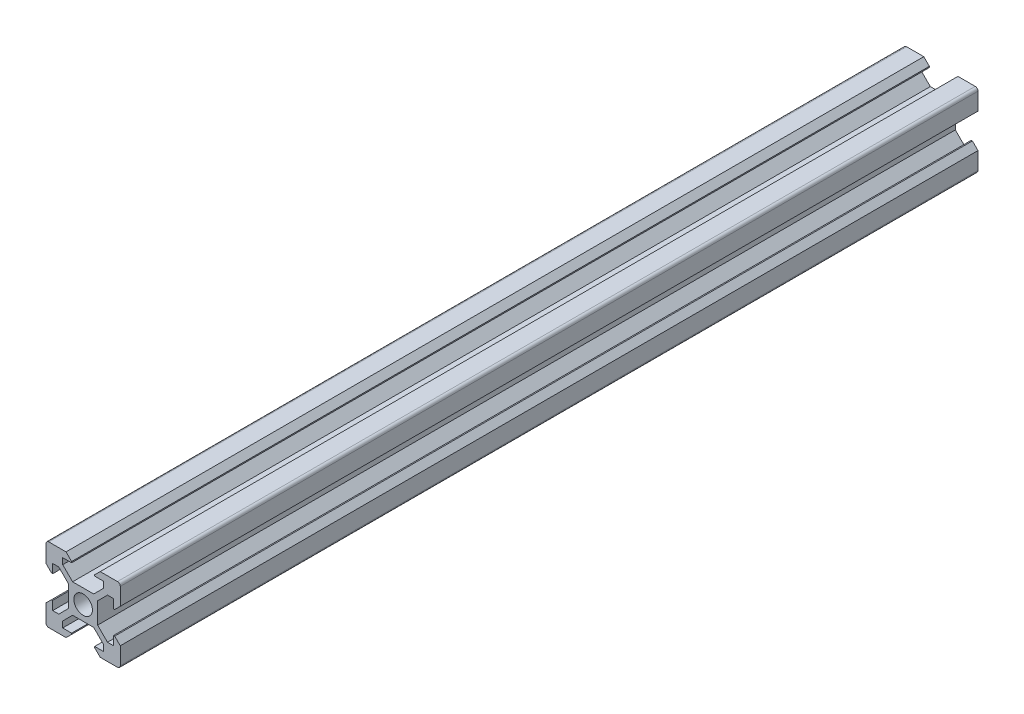
SolidWorks part; units mm, degrees
other "Markup1"
sketch "Sketch1" plane through (10, 10, 480) normal (0.5774, 0.5773, 0.5774) x (0.7071, 0, -0.7071)
ref_plane "Alzado" through (0, 0, 0) normal (0, 0, 1) x (1, 0, 0)
ref_plane "Planta" through (0, 0, 0) normal (0, 1, 0) x (1, 0, 0)
ref_plane "Vista lateral" through (0, 0, 0) normal (1, 0, 0) x (0, 0, -1)
sketch "Croquis1" plane through (0, 0, 0) normal (0, 0, 1) x (1, 0, 0)
  line L0 (-4.6, 10) -> (-3.1, 8.5)
  line L3 (-4.6, 10) -> (-9.25, 10)
  line L5 (-3.1, 8.5) -> (-3.1, 8.2)
  line L6 (-3.1, 8.2) -> (-5.5, 8.2)
  line L7 (-5.5, 8.2) -> (-5.5, 6.5607)
  line L8 (-5.5, 6.5607) -> (-2.84, 3.9007)
  line L9 (-2.84, 3.9007) -> (0, 3.9007)
  line L10 (0, 0) -> (-15.3499, 15.3499) construction
  line L11 (-3.9007, 2.84) -> (-3.9007, 0)
  line L12 (-6.5607, 5.5) -> (-3.9007, 2.84)
  line L13 (-8.2, 5.5) -> (-6.5607, 5.5)
  line L14 (-8.2, 3.1) -> (-8.2, 5.5)
  line L15 (-8.5, 3.1) -> (-8.2, 3.1)
  line L16 (-10, 4.6) -> (-10, 9.25)
  line L17 (-10, 4.6) -> (-8.5, 3.1)
  line L18 (10, 4.6) -> (8.5, 3.1)
  line L19 (10, 4.6) -> (10, 9.25)
  line L20 (8.5, 3.1) -> (8.2, 3.1)
  line L21 (8.2, 3.1) -> (8.2, 5.5)
  line L22 (8.2, 5.5) -> (6.5607, 5.5)
  line L23 (6.5607, 5.5) -> (3.9007, 2.84)
  line L24 (3.9007, 2.84) -> (3.9007, 0)
  line L25 (5.5, 6.5607) -> (2.84, 3.9007)
  line L26 (5.5, 8.2) -> (5.5, 6.5607)
  line L27 (3.1, 8.2) -> (5.5, 8.2)
  line L28 (3.1, 8.5) -> (3.1, 8.2)
  line L29 (4.6, 10) -> (9.25, 10)
  line L30 (4.6, 10) -> (3.1, 8.5)
  line L31 (2.84, 3.9007) -> (0, 3.9007)
  line L32 (4.6, -10) -> (3.1, -8.5)
  line L33 (4.6, -10) -> (9.25, -10)
  line L34 (3.1, -8.5) -> (3.1, -8.2)
  line L35 (3.1, -8.2) -> (5.5, -8.2)
  line L36 (5.5, -8.2) -> (5.5, -6.5607)
  line L37 (5.5, -6.5607) -> (2.84, -3.9007)
  line L38 (2.84, -3.9007) -> (0, -3.9007)
  line L39 (6.5607, -5.5) -> (3.9007, -2.84)
  line L40 (8.2, -5.5) -> (6.5607, -5.5)
  line L41 (8.2, -3.1) -> (8.2, -5.5)
  line L42 (8.5, -3.1) -> (8.2, -3.1)
  line L43 (10, -4.6) -> (10, -9.25)
  line L44 (10, -4.6) -> (8.5, -3.1)
  line L45 (3.9007, -2.84) -> (3.9007, 0)
  line L46 (-10, -4.6) -> (-8.5, -3.1)
  line L47 (-10, -4.6) -> (-10, -9.25)
  line L48 (-8.5, -3.1) -> (-8.2, -3.1)
  line L49 (-8.2, -3.1) -> (-8.2, -5.5)
  line L50 (-8.2, -5.5) -> (-6.5607, -5.5)
  line L51 (-6.5607, -5.5) -> (-3.9007, -2.84)
  line L52 (-3.9007, -2.84) -> (-3.9007, 0)
  line L53 (-5.5, -6.5607) -> (-2.84, -3.9007)
  line L54 (-5.5, -8.2) -> (-5.5, -6.5607)
  line L55 (-3.1, -8.2) -> (-5.5, -8.2)
  line L56 (-3.1, -8.5) -> (-3.1, -8.2)
  line L57 (-4.6, -10) -> (-9.25, -10)
  line L58 (-4.6, -10) -> (-3.1, -8.5)
  line L59 (-2.84, -3.9007) -> (0, -3.9007)
  circle A0 centre (0, 0) radius 2.5
  arc A1 (-9.25, 10) -> (-10, 9.25) centre (-9.25, 9.25) ccw
  arc A2 (10, 9.25) -> (9.25, 10) centre (9.25, 9.25) ccw
  arc A3 (9.25, -10) -> (10, -9.25) centre (9.25, -9.25) ccw
  arc A4 (-10, -9.25) -> (-9.25, -10) centre (-9.25, -9.25) ccw
  point P18 (-10, 10)
  point P37 (10, 10)
  point P55 (10, -10)
  point P73 (-10, -10)
  point P79 (0, 0)
  dimension "D1" = 5
  dimension "D5" = 0.75
  dimension "D2" = 10
  dimension "D3" = 10
  dimension "D4" = 4.6
  dimension "D6" = 5.5
  dimension "D7" = 135
  dimension "D8" = 0.75
  dimension "D9" = 225
  dimension "D10" = 2.84
  dimension "D11" = 1.8
  dimension "D12" = 3.1
  dimension "D13" = 4
extrude "Saliente-Extruir1" add sketch "Croquis1" along normal blind 480
sketch "Sketch2" plane through (0, 0, 0) normal (1, 0, 0) x (0, 0, -1)
  line L0 (-249, 40.7698) -> (-249, -37.1573) construction
  line L1 (-249, -13.3929) -> (249, -13.3929)
  line L2 (-249, -13.3929) -> (-249, 13.3929)
  line L3 (-249, 13.3929) -> (249, 13.3929)
  line L4 (249, -13.3929) -> (249, 13.3929)
  line L5 (-249, -13.3929) -> (249, 13.3929) construction
  line L6 (-249, 13.3929) -> (249, -13.3929) construction
  line L7 (-480, -2.84) -> (-480, 2.84) construction
  point P0 (0, 0)
  dimension "D1" = 231
extrude "Cut-Extrude1" cut sketch "Sketch2" against normal blind 24 and the other way blind 25 contours L2 L1 L4 L3
